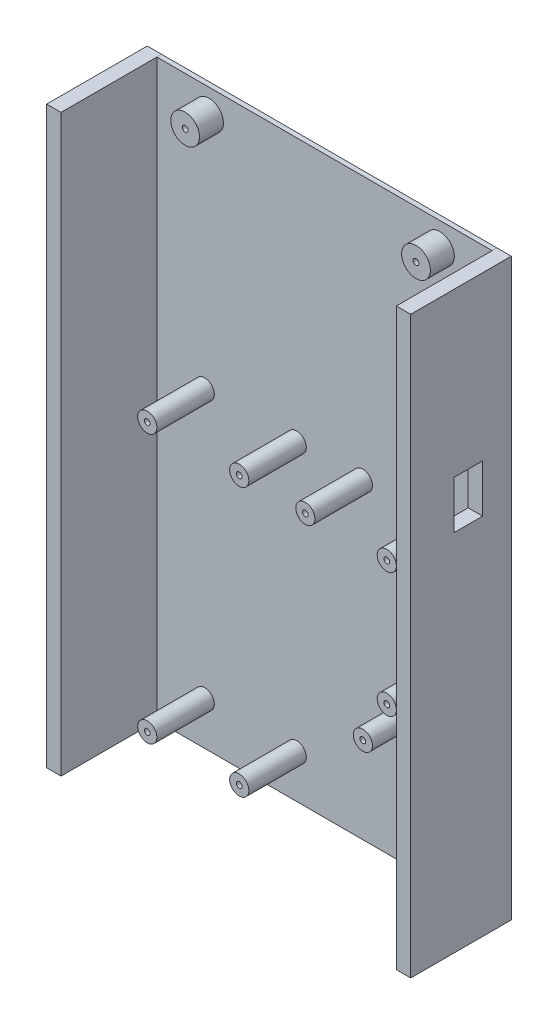
SolidWorks part; units mm, degrees
ref_plane "Přední rovina" through (0, 0, 0) normal (0, 0, 1) x (1, 0, 0)
ref_plane "Horní rovina" through (0, 0, 0) normal (0, 1, 0) x (1, 0, 0)
ref_plane "Pravá rovina" through (0, 0, 0) normal (1, 0, 0) x (0, 0, -1)
sketch "Skica1" plane through (0, 0, 0) normal (0, 0, 1) x (1, 0, 0)
  line L1 (0, 0) -> (70, 0)
  line L2 (0, 0) -> (0, 120)
  line L3 (0, 120) -> (70, 120)
  line L4 (70, 0) -> (70, 120)
  dimension "D1" = 120
  dimension "D2" = 70
extrude "Přidat vysunutím1" add sketch "Skica1" along normal blind 1
sketch "Skica2" plane through (0, 0, 1) normal (0, 0, 1) x (1, 0, 0)
  line L4 (70, 120) -> (0, 120) construction
  line L5 (0, 120) -> (0, 0) construction
  line L9 (70, 0) -> (70, 120) construction
  line L10 (0, 0) -> (70, 0) construction
  circle A0 centre (59.1, 115) radius 0.6
  circle A1 centre (10.9, 115) radius 0.6
  circle A2 centre (10, 65) radius 0.6
  circle A3 centre (29.2, 65) radius 0.6
  circle A4 centre (10, 9) radius 0.6
  circle A5 centre (29.2, 9) radius 0.6
  circle A6 centre (43, 65) radius 0.6
  circle A7 centre (60, 65) radius 0.6
  circle A8 centre (60, 39) radius 0.6
  circle A9 centre (55, 30) radius 0.6
  circle A10 centre (10, 65) radius 2
  circle A11 centre (29.2, 65) radius 2
  circle A12 centre (43, 65) radius 2
  circle A13 centre (60, 65) radius 2
  circle A14 centre (60, 39) radius 2
  circle A15 centre (55, 30) radius 2
  circle A16 centre (29.2, 9) radius 2
  circle A17 centre (10, 9) radius 2
  circle A18 centre (10.9, 115) radius 3
  circle A19 centre (59.1, 115) radius 3
  dimension "D1" = 1.2
  dimension "D2" = 1.2
  dimension "D3" = 48.2
  dimension "D4" = 5
  dimension "D5" = 10.9
  dimension "D6" = 5
  dimension "D7" = 1.2
  dimension "D8" = 1.2
  dimension "D9" = 1.2
  dimension "D10" = 1.2
  dimension "D11" = 1.2
  dimension "D12" = 1.2
  dimension "D13" = 1.2
  dimension "D14" = 56
  dimension "D15" = 56
  dimension "D16" = 50
  dimension "D17" = 50
  dimension "D18" = 19.2
  dimension "D19" = 19.2
  dimension "D20" = 10
  dimension "D21" = 9
  dimension "D22" = 26
  dimension "D23" = 0
  dimension "D24" = 17
  dimension "D25" = 10
  dimension "D26" = 50
  dimension "D27" = 39
  dimension "D28" = 30
  dimension "D29" = 1.2
  dimension "D30" = 15
  dimension "D31" = 4
  dimension "D32" = 4
  dimension "D33" = 4
  dimension "D34" = 4
  dimension "D35" = 4
  dimension "D36" = 4
  dimension "D37" = 4
  dimension "D38" = 4
  dimension "D39" = 6
  dimension "D40" = 6
extrude "Přidat vysunutím2" add sketch "Skica2" along normal blind 12
sketch "Skica4" plane through (0, 0, 1) normal (0, 0, 1) x (1, 0, 0)
  line L1 (0, 0) -> (-3, 0)
  line L2 (0, 0) -> (0, 120)
  line L3 (0, 120) -> (-3, 120)
  line L4 (-3, 0) -> (-3, 120)
  line L25 (35, 128.5362) -> (35, -20.7413) construction
  line L34 (73, 0) -> (73, 120)
  line L52 (70, 120) -> (73, 120)
  line L53 (70, 0) -> (70, 120)
  line L54 (70, 0) -> (73, 0)
  point P10 (0, 0)
  dimension "D4" = 120
  dimension "D12" = 35
  dimension "D14" = 3
extrude "Přidat vysunutím3" add sketch "Skica4" along normal blind 20 and the other way blind 1 separate body
sketch "Skica5" plane through (73, 0, 0) normal (1, 0, 0) x (0, 0, -1)
  line L0 (0, 0) -> (0, 120) construction
  line L1 (-12, 76) -> (-6, 76)
  line L2 (-12, 76) -> (-12, 86)
  line L3 (-12, 86) -> (-6, 86)
  line L4 (-6, 76) -> (-6, 86)
  line L5 (-12, 86) -> (-6, 86)
  line L6 (0, 120) -> (-21, 120) construction
  dimension "D1" = 34
  dimension "D2" = 10
  dimension "D3" = 6
  dimension "D4" = 6
extrude "Odebrat vysunutím2" cut sketch "Skica5" against normal blind 20 contours L3 L4 L1 L2
sketch "Skica6" plane through (0, 0, 13) normal (0, 0, 1) x (1, 0, 0)
  circle A0 centre (10.9, 115) radius 3
  circle A1 centre (59.1, 115) radius 3
  dimension "D1" = 6
  dimension "D2" = 6
extrude "Odebrat vysunutím3" cut sketch "Skica6" against normal blind 7
